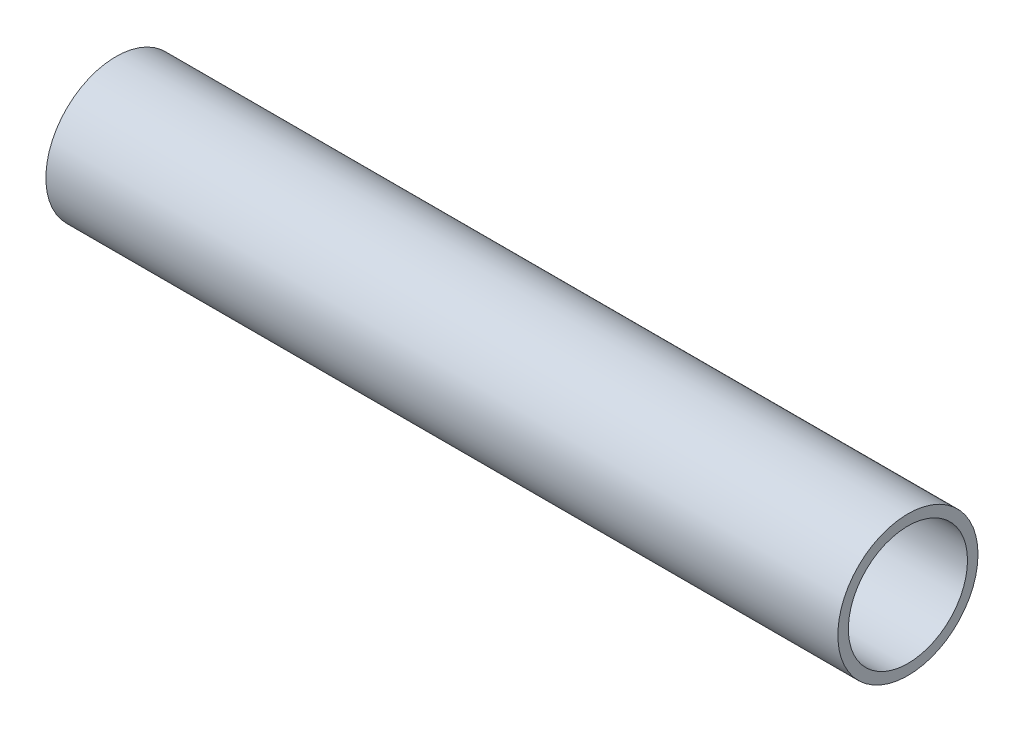
SolidWorks part; units mm, degrees
ref_plane "前视基准面" through (0, 0, 0) normal (0, 0, 1) x (1, 0, 0)
ref_plane "上视基准面" through (0, 0, 0) normal (0, 1, 0) x (1, 0, 0)
ref_plane "右视基准面" through (0, 0, 0) normal (1, 0, 0) x (0, 0, -1)
sketch "草图1" plane through (0, 0, 0) normal (1, 0, 0) x (0, 0, -1)
  circle A0 centre (0, 0) radius 10
  circle A1 centre (0, 0) radius 8.5
  dimension "D1" = 20
  dimension "D2" = 17
extrude "凸台-拉伸1" add sketch "草图1" along normal blind 113
